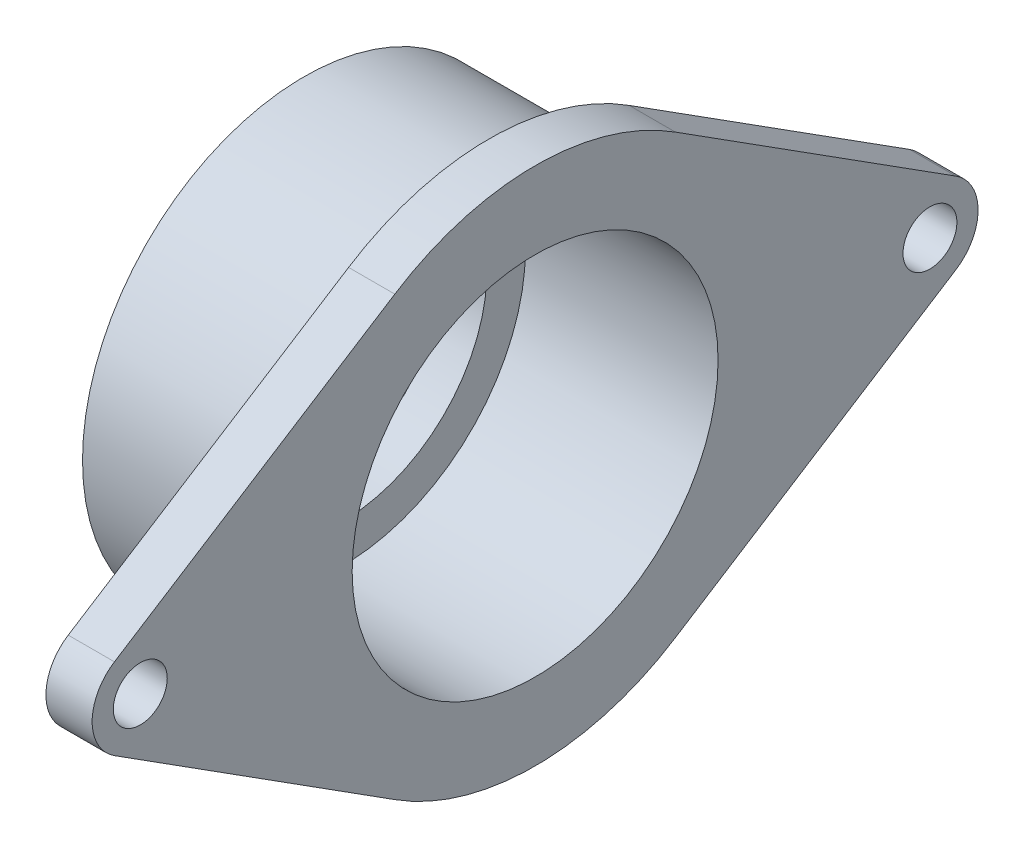
SolidWorks part; units mm, degrees
material "ASTM A36 Steel"
ref_plane "Front Plane" through (0, 0, 0) normal (0, 0, 1) x (1, 0, 0)
ref_plane "Top Plane" through (0, 0, 0) normal (0, 1, 0) x (1, 0, 0)
ref_plane "Right Plane" through (0, 0, 0) normal (1, 0, 0) x (0, 0, -1)
sketch "Sketch1" plane through (0, 0, 0) normal (0, 0, 1) x (1, 0, 0)
  line L0 (-25.894, 44.6417) -> (-85.894, 44.6417)
  line L1 (-85.894, 44.6417) -> (-85.894, 24.6417)
  line L2 (-85.894, 24.6417) -> (-75.894, 24.6417)
  line L3 (-75.894, 24.6417) -> (-75.894, 34.6417)
  line L4 (-75.894, 34.6417) -> (-25.894, 34.6417)
  line L5 (-25.894, 34.6417) -> (-25.894, 44.6417)
  line L6 (-85.894, -12.8583) -> (31.0177, -12.8583)
  dimension "D1" = 37.5
  dimension "D2" = 10
  dimension "D3" = 10
  dimension "D4" = 60
  dimension "D5" = 10
revolve "Revolve1" add sketch "Sketch1" angle 360 about L6
sketch "Sketch2" plane through (-25.894, 0, 0) normal (1, 0, 0) x (0, 0, -1)
  line L2 (36.4251, -69.6866) -> (109.2073, -23.4064)
  line L3 (36.4251, 43.9701) -> (109.2073, -2.3102)
  line L5 (-36.4251, 43.9701) -> (-109.2073, -2.3102)
  line L6 (-36.4251, -69.6866) -> (-109.2073, -23.4064)
  circle A0 centre (0, -12.8583) radius 57.5
  arc A1 (-36.4251, -69.6866) -> (36.4251, -69.6866) centre (0, -12.8583) ccw
  arc A2 (109.2073, -23.4064) -> (109.2073, -2.3102) centre (102.5, -12.8583) ccw
  arc A3 (-109.2073, -2.3102) -> (-109.2073, -23.4064) centre (-102.5, -12.8583) ccw
  arc A4 (36.4251, 43.9701) -> (-36.4251, 43.9701) centre (0, -12.8583) ccw
  dimension "D1" = 135
  dimension "D4" = 25
  dimension "D5" = 25
extrude "Boss-Extrude1" add sketch "Sketch2" against normal blind 12
sketch "Sketch3" plane through (-25.894, 0, 0) normal (1, 0, 0) x (0, 0, -1)
  circle A0 centre (-102.5, -12.8583) radius 7
  circle A1 centre (102.5, -12.8583) radius 7
  dimension "D1" = 14
  dimension "D2" = 14
extrude "Cut-Extrude1" cut sketch "Sketch3" against normal blind 12
